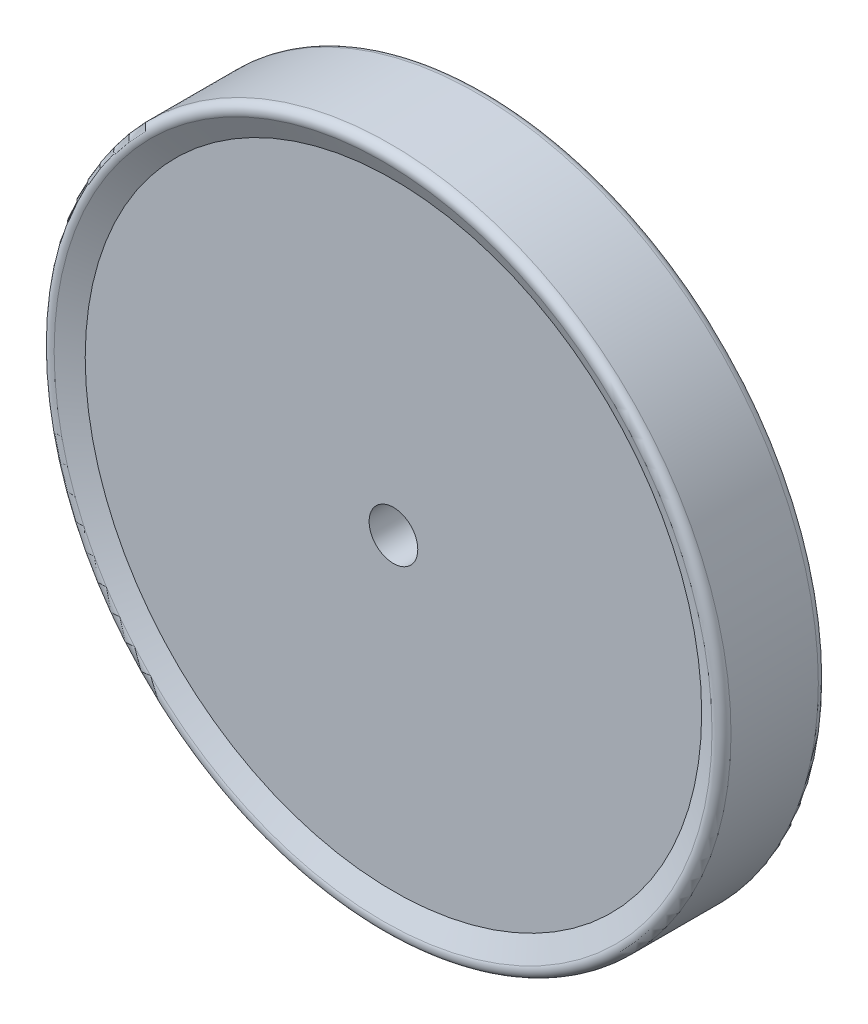
SolidWorks part; units mm, degrees
ref_plane "Front Plane" through (0, 0, 0) normal (0, 0, 1) x (1, 0, 0)
ref_plane "Top Plane" through (0, 0, 0) normal (0, 1, 0) x (1, 0, 0)
ref_plane "Right Plane" through (0, 0, 0) normal (1, 0, 0) x (0, 0, -1)
sketch "Sketch1" plane through (0, 0, 0) normal (0, 0, 1) x (1, 0, 0)
  circle A0 centre (0, 0) radius 19
  circle A1 centre (0, 0) radius 1.5
  dimension "D1" = 38
  dimension "D2" = 3
extrude "Boss-Extrude1" add sketch "Sketch1" along normal blind 5
sketch "Sketch2" plane through (0, 0, 0) normal (0, 1, 0) x (1, 0, 0)
  line L0 (0, 0) -> (0, -5) construction
  line L1 (-19, -5) -> (19, -5) construction
  line L2 (21, -6) -> (21, 1)
  line L3 (21, 1) -> (19, 0)
  line L4 (19, 0) -> (19, -5)
  line L5 (19, -5) -> (21, -6)
  point P8 (21, -2.5)
  point P9 (0, -2.5)
  dimension "D1" = 7
  dimension "D2" = 2
revolve "Revolve2" add sketch "Sketch2" angle 360 about L0
fillet "Fillet1" radius 0.5 2 edges at (-21, 0, 6) (-21, 0, -1)
